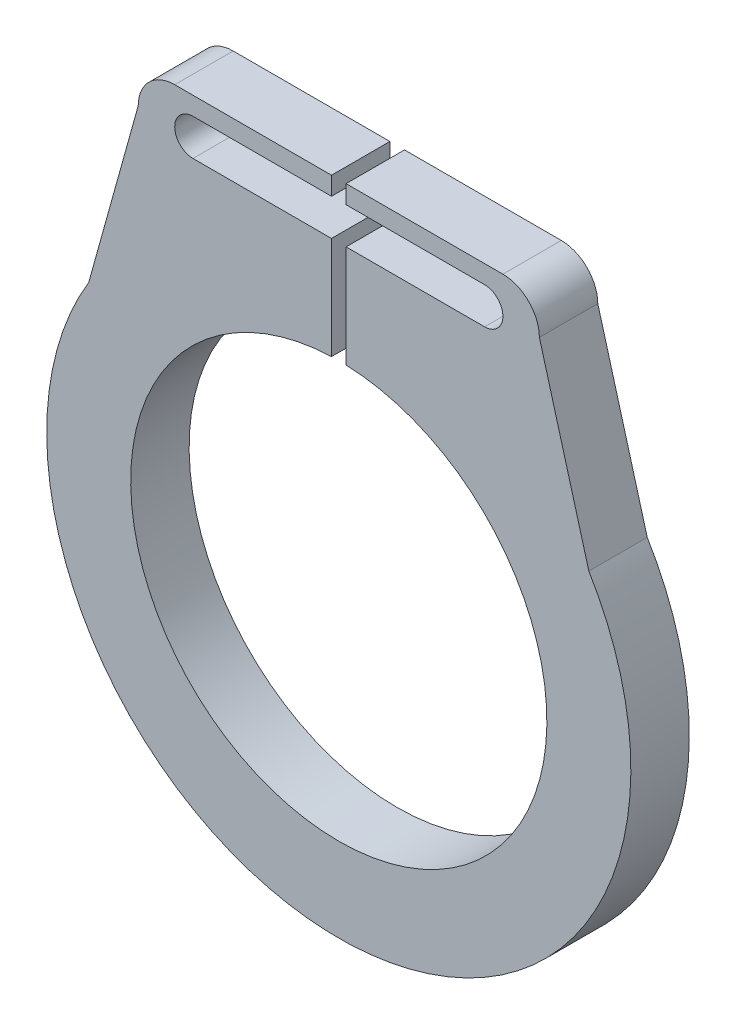
SolidWorks part; units mm, degrees
ref_plane "Front Plane" through (0, 0, 0) normal (0, 0, 1) x (1, 0, 0)
ref_plane "Top Plane" through (0, 0, 0) normal (0, 1, 0) x (1, 0, 0)
ref_plane "Right Plane" through (0, 0, 0) normal (1, 0, 0) x (0, 0, -1)
sketch "Sketch1" plane through (0, 0, 0) normal (0, 0, 1) x (1, 0, 0)
  line L0 (0, -1000) -> (0, -1.425) construction
  line L1 (-0.05, 1.4241) -> (-0.05, 2.5)
  line L2 (0.05, 1.4241) -> (0.05, 2.5)
  line L3 (0.9985, 2.25) -> (0.05, 2.25) construction
  line L4 (0.9985, 2.125) -> (0.05, 2.125)
  line L5 (0.9985, 2.375) -> (0.05, 2.375)
  line L6 (-1.1235, 2.25) -> (-0.05, 2.25) construction
  line L7 (-1.1235, 2.5) -> (-0.05, 2.5)
  line L9 (-1.3735, 2.25) -> (-1.7122, 1.0336)
  line L10 (1.7122, 1.0336) -> (1.3735, 2.25)
  line L11 (0, 2) -> (0, 2.5) construction
  line L13 (-0.05, 2.125) -> (-0.9985, 2.125)
  line L14 (-0.05, 2.25) -> (-0.9985, 2.25) construction
  line L15 (0.05, 2.25) -> (1.1235, 2.25) construction
  line L16 (-0.05, 2.375) -> (-0.9985, 2.375)
  line L17 (0.05, 2.5) -> (1.1235, 2.5)
  arc A0 (-0.05, 1.4241) -> (0.05, 1.4241) centre (0, 0) ccw
  arc A1 (0.9985, 2.125) -> (0.9985, 2.375) centre (0.9985, 2.25) ccw
  arc A2 (-0.9985, 2.375) -> (-0.9985, 2.125) centre (-0.9985, 2.25) ccw
  arc A3 (-1.1235, 2.5) -> (-1.3735, 2.25) centre (-1.1235, 2.25) ccw
  arc A4 (1.3735, 2.25) -> (1.1235, 2.5) centre (1.1235, 2.25) ccw
  arc A5 (-1.7122, 1.0336) -> (1.7122, 1.0336) centre (0, 0) ccw
  point P9 (0, 2.25)
  point P16 (0, 2.25)
extrude "Boss-Extrude2" add sketch "Sketch1" along normal blind 0.4 contours L9 A5 L10 A4 L17 L2 L5 A1 L4 A0 L1 L13 A2 L16 L7 A3
